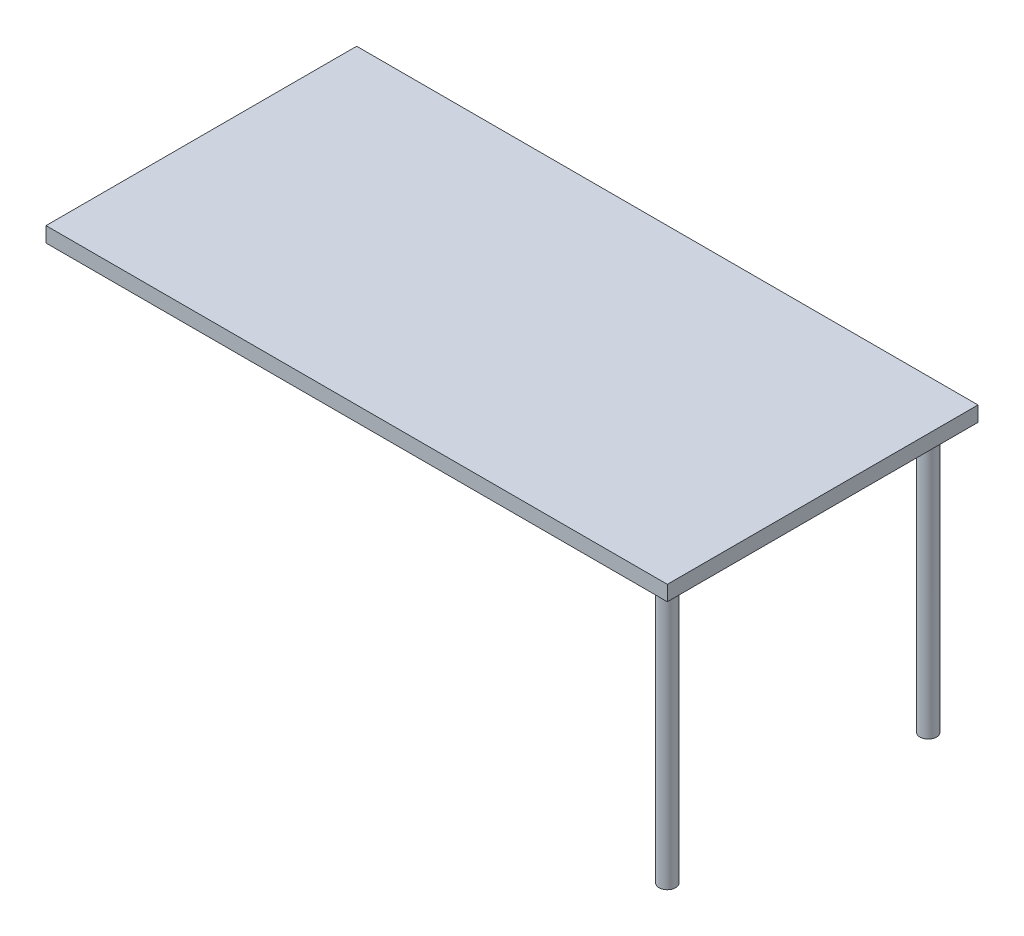
SolidWorks part; units mm, degrees
ref_plane "Front Plane" through (0, 0, 0) normal (0, 0, 1) x (1, 0, 0)
ref_plane "Top Plane" through (0, 0, 0) normal (0, 1, 0) x (1, 0, 0)
ref_plane "Right Plane" through (0, 0, 0) normal (1, 0, 0) x (0, 0, -1)
sketch "Sketch1" plane through (0, 0, 0) normal (0, 1, 0) x (1, 0, 0)
  line L1 (-750, -375) -> (750, -375)
  line L2 (-750, -375) -> (-750, 375)
  line L3 (-750, 375) -> (750, 375)
  line L4 (750, -375) -> (750, 375)
  line L5 (-750, -375) -> (750, 375) construction
  line L6 (-750, 375) -> (750, -375) construction
  point P0 (0, 0)
  dimension "D1" = 1500
  dimension "D2" = 750
extrude "Boss-Extrude1" add sketch "Sketch1" along normal blind 36.5
sketch "Sketch2" plane through (0, 0, 0) normal (0, -1, 0) x (1, 0, 0)
  line L0 (-750, 375) -> (750, 375) construction
  line L1 (750, 375) -> (750, -375) construction
  circle A0 centre (690, 315) radius 20
  dimension "D1" = 40
  dimension "D3" = 60
  dimension "D2" = 60
extrude "Boss-Extrude2" add sketch "Sketch2" along normal blind 648
mirror "Mirror1" about plane through (0, 0, 0) normal (0, 0, 1) of "Boss-Extrude2"
